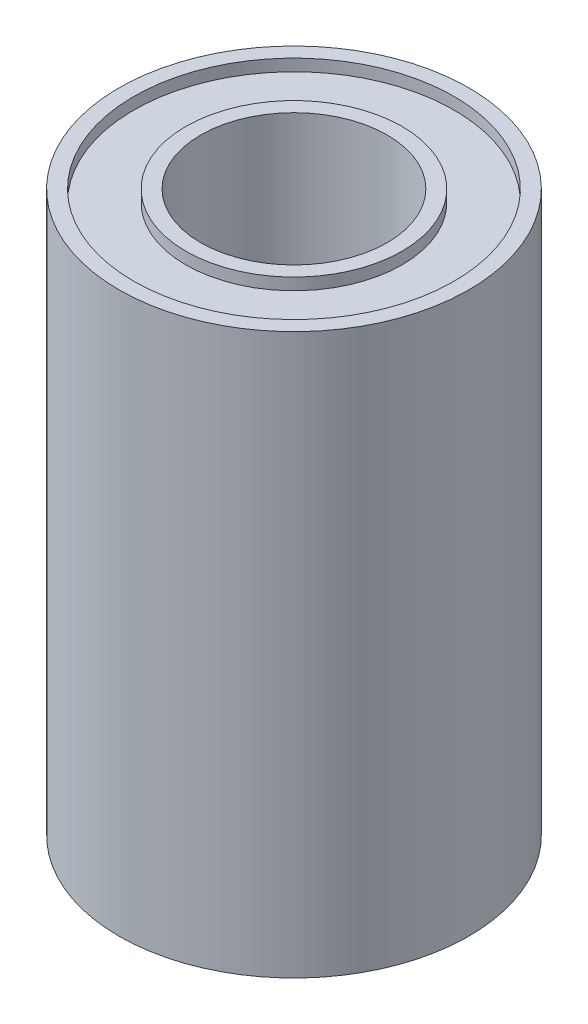
SolidWorks part; units mm, degrees
other "Markup1"
sketch "Sketch3" plane through (7.5, 12, -7.5) normal (0.0347, 0.9337, -0.3564) x (0.5403, 0.2825, 0.7927)
material "6061-O (SS)"
ref_plane "Front Plane" through (0, 0, 0) normal (0, 0, 1) x (1, 0, 0)
ref_plane "Top Plane" through (0, 0, 0) normal (0, 1, 0) x (1, 0, 0)
ref_plane "Right Plane" through (0, 0, 0) normal (1, 0, 0) x (0, 0, -1)
sketch "Sketch1" plane through (0, 0, 0) normal (0, 1, 0) x (1, 0, 0)
  circle A0 centre (0, 0) radius 4
  circle A1 centre (0, 0) radius 7.5
  dimension "D1" = 8
  dimension "D2" = 15
extrude "Boss-Extrude1" add sketch "Sketch1" along normal mid plane 24
sketch "Sketch2" plane through (0, 12, 0) normal (0, 1, 0) x (1, 0, 0)
  circle A0 centre (0, 0) radius 4.635
  circle A1 centre (0, 0) radius 6.865
  circle A2 centre (0, 0) radius 4 construction
  circle A3 centre (0, 0) radius 7.5 construction
  dimension "D1" = 0.635
  dimension "D2" = 0.635
extrude "Cut-Extrude1" cut sketch "Sketch2" against normal blind 0.508
mirror "Mirror1" about plane through (0, 0, 0) normal (0, 1, 0) of "Cut-Extrude1"
